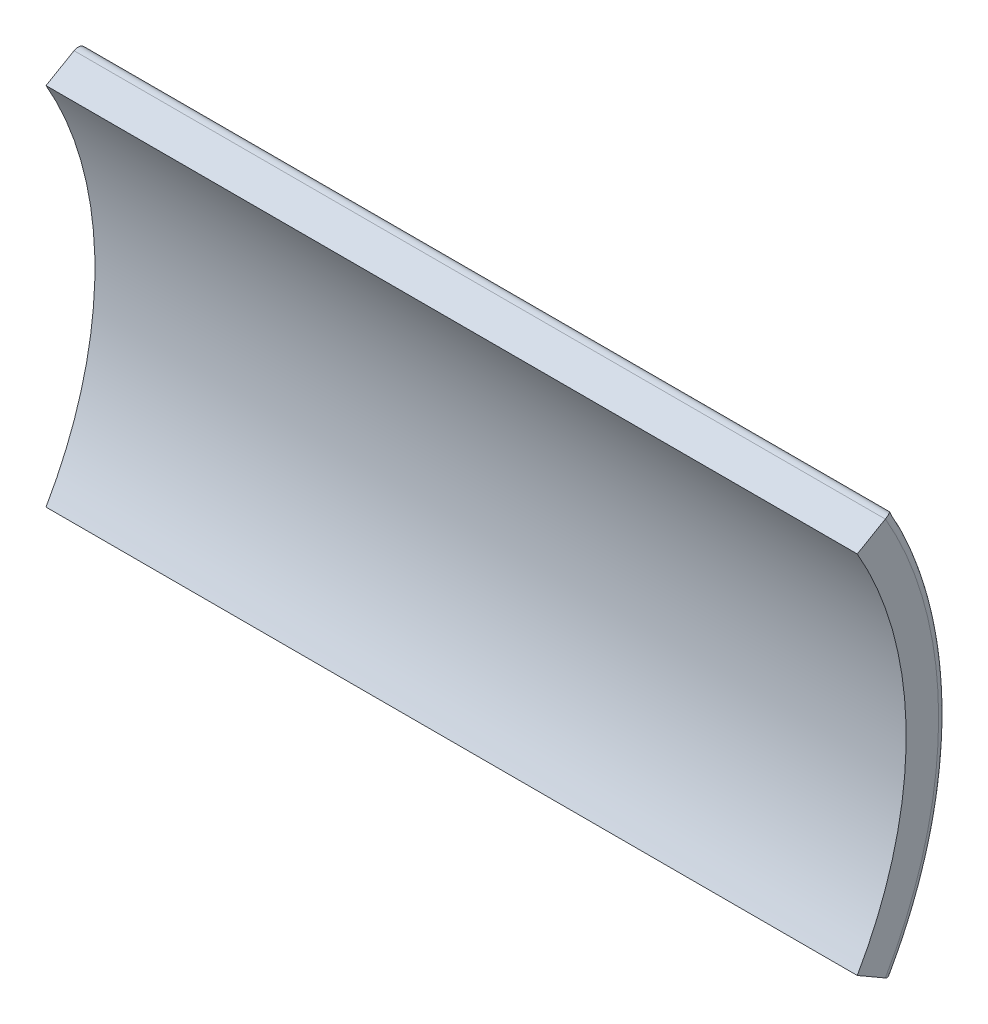
SolidWorks part; units mm, degrees
ref_plane "Front Plane" through (0, 0, 0) normal (0, 0, 1) x (1, 0, 0)
ref_plane "Top Plane" through (0, 0, 0) normal (0, 1, 0) x (1, 0, 0)
ref_plane "Right Plane" through (0, 0, 0) normal (1, 0, 0) x (0, 0, -1)
sketch "airflap" plane through (0, 0, 0) normal (1, 0, 0) x (0, 0, -1)
  line L0 (0, 0) -> (0, 5) construction
  line L1 (0, 0) -> (0, -5) construction
  line L2 (3.8971, 2.25) -> (4.3301, 2.5)
  line L3 (-4.3301, -2.5) -> (4.3301, -2.5) construction
  line L4 (-4.3301, -2.5) -> (-4.3301, 2.5) construction
  line L5 (-4.3301, 2.5) -> (4.3301, 2.5) construction
  line L6 (4.3301, -2.5) -> (4.3301, 2.5) construction
  line L7 (-4.3301, -2.5) -> (4.3301, 2.5) construction
  line L8 (-4.3301, 2.5) -> (4.3301, -2.5) construction
  line L9 (4.3301, -2.5) -> (3.8971, -2.25)
  arc A0 (4.3301, 2.5) -> (4.3301, -2.5) centre (0, 0) cw
  arc A1 (3.8971, 2.25) -> (3.8971, -2.25) centre (0, 0) cw
  dimension "D2" = 5
  dimension "D3" = 5
  dimension "D4" = 4.5
  dimension "D1" = 5
extrude "Boss-Extrude1" add sketch "airflap" along normal blind 10
fillet "Fillet3" radius 0.1 3 edges at (5, -2.5, -4.3301) (5, 2.5, -4.3301) (10, 0, -5)
